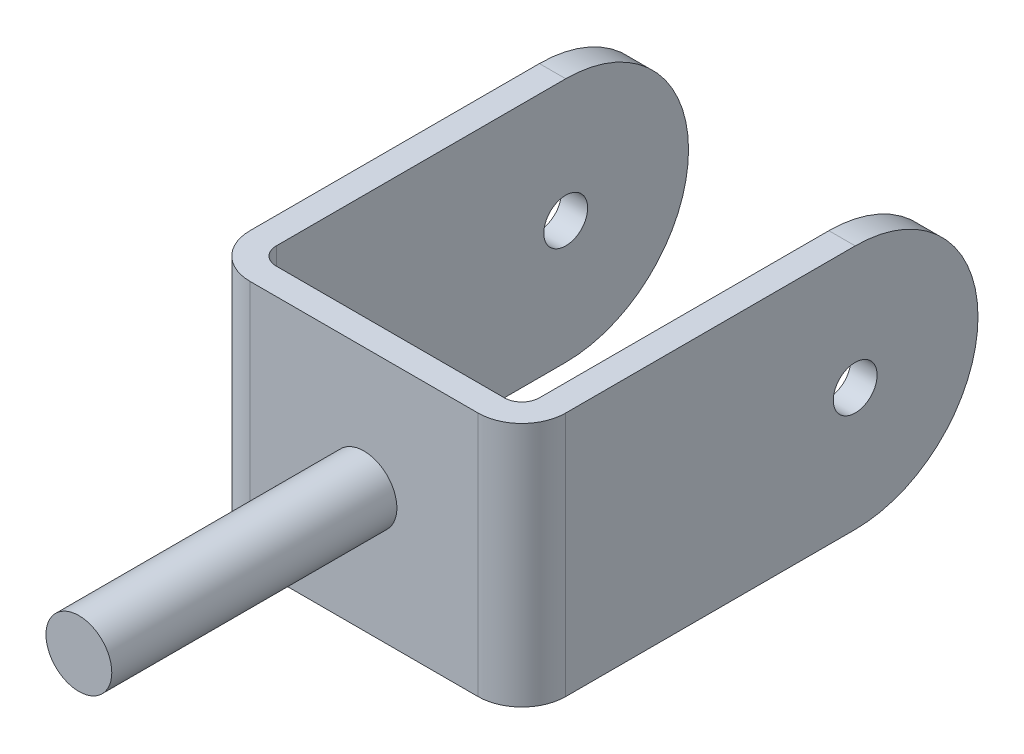
SolidWorks part; units mm, degrees
ref_plane "Front Plane" through (0, 0, 0) normal (0, 0, 1) x (1, 0, 0)
ref_plane "Top Plane" through (0, 0, 0) normal (0, 1, 0) x (1, 0, 0)
ref_plane "Right Plane" through (0, 0, 0) normal (1, 0, 0) x (0, 0, -1)
sketch "Sketch1" plane through (0, 0, 0) normal (0, 1, 0) x (1, 0, 0)
  line L0 (-407.8173, 0) -> (407.8173, 0) construction
  line L1 (0, 303.8503) -> (0, -303.8503) construction
  line L2 (-130, 0) -> (130, 0)
  line L3 (-180, 50) -> (-180, 520)
  line L4 (180, 50) -> (180, 520)
  line L5 (150, 50) -> (150, 520)
  line L6 (-130, 30) -> (130, 30)
  line L7 (-150, 50) -> (-150, 520)
  line L8 (-180, 520) -> (-150, 520)
  line L9 (180, 520) -> (150, 520)
  arc A0 (130, 0) -> (180, 50) centre (130, 50) ccw
  arc A1 (-130, 0) -> (-180, 50) centre (-130, 50) cw
  arc A2 (130, 30) -> (150, 50) centre (130, 50) ccw
  arc A3 (-130, 30) -> (-150, 50) centre (-130, 50) cw
  point P5 (0, 0)
  point P8 (0, 0)
  point P13 (180, 0)
  point P16 (-180, 0)
  dimension "D3" = 50
  dimension "D1" = 360
  dimension "D2" = 520
  dimension "D4" = 30
extrude "Boss-Extrude1" add sketch "Sketch1" along normal blind 280
sketch "Sketch2" plane through (0, 0, 0) normal (0, 0, 1) x (1, 0, 0)
  line L1 (-180, 280) -> (-180, 0) construction
  line L2 (-130, 0) -> (130, 0) construction
  circle A0 centre (0, 140) radius 37.5
  dimension "D1" = 75
  dimension "D2" = 140
  dimension "D3" = 180
extrude "Boss-Extrude2" add sketch "Sketch2" along normal blind 325
sketch "Sketch4" plane through (180, 0, 0) normal (1, 0, 0) x (0, 0, -1)
  line L0 (380, 174.298) -> (380, -21.3206) construction
  line L1 (50, 280) -> (520, 280) construction
  line L2 (50, 0) -> (520, 0) construction
  line L3 (520, 280) -> (520, 0) construction
  line L4 (380, 174.298) -> (380, -37.6745) construction
  line L5 (0, 280) -> (0, 0) construction
  line L6 (380, 280) -> (520, 280)
  line L7 (520, 280) -> (520, 0)
  line L8 (520, 0) -> (380, 0)
  line L9 (200.4235, 140) -> (638.4393, 140) construction
  arc A0 (380, 0) -> (380, 280) centre (380, 140) ccw
  circle A1 centre (380, 140) radius 25
  line M6 (50, 0) -> (520, 0)
  line M7 (520, 0) -> (520, 280)
  line M8 (520, 280) -> (50, 280)
  dimension "D1" = 380
  dimension "D2" = 50
extrude "Cut-Extrude1" cut sketch "Sketch4" against normal through all contours A1 | A0 L7 M8 | A0 M6 M7
